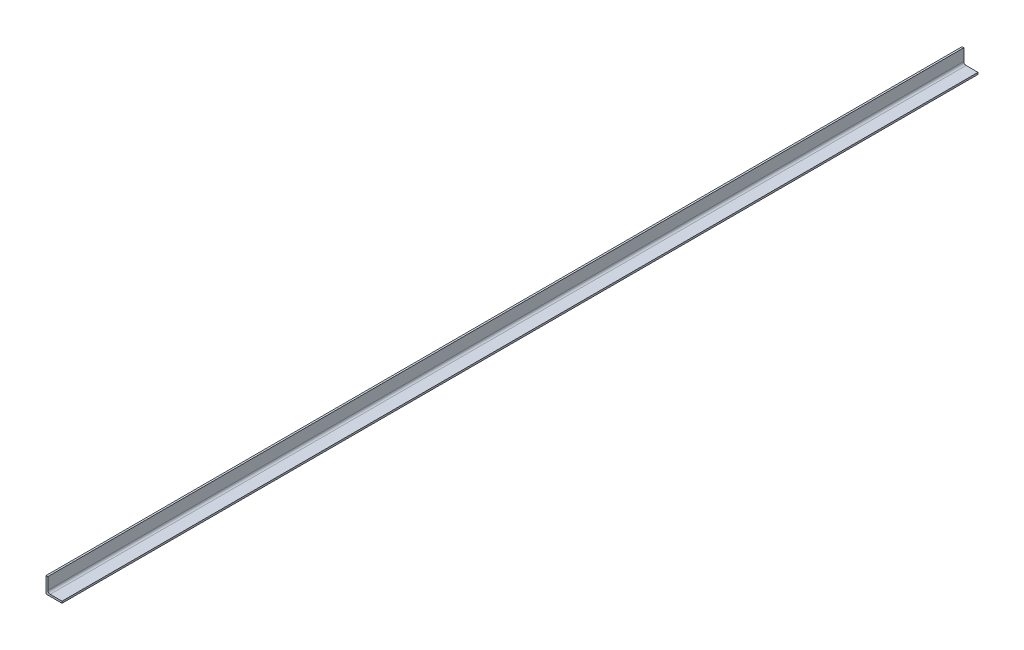
SolidWorks part; units mm, degrees
ref_plane "Front" through (0, 0, 0) normal (0, 0, 1) x (1, 0, 0)
ref_plane "Top" through (0, 0, 0) normal (0, 1, 0) x (1, 0, 0)
ref_plane "Right" through (0, 0, 0) normal (1, 0, 0) x (0, 0, -1)
sketch "Esquisse1" plane through (0, 0, 0) normal (0, 0, 1) x (1, 0, 0)
  line L0 (0, 0) -> (0, 35)
  line L1 (0, 35) -> (4, 35)
  line L2 (4, 35) -> (4, 4)
  line L3 (4, 4) -> (35, 4)
  line L4 (35, 4) -> (35, 0)
  line L5 (35, 0) -> (0, 0)
  dimension "D1" = 4
  dimension "D2" = 4
  dimension "D3" = 35
  dimension "D4" = 35
extrude "Boss.-Extru.1" add sketch "Esquisse1" along normal blind 2000
fillet "Congé1" radius 5 1 edges at (4, 4, 1000)
